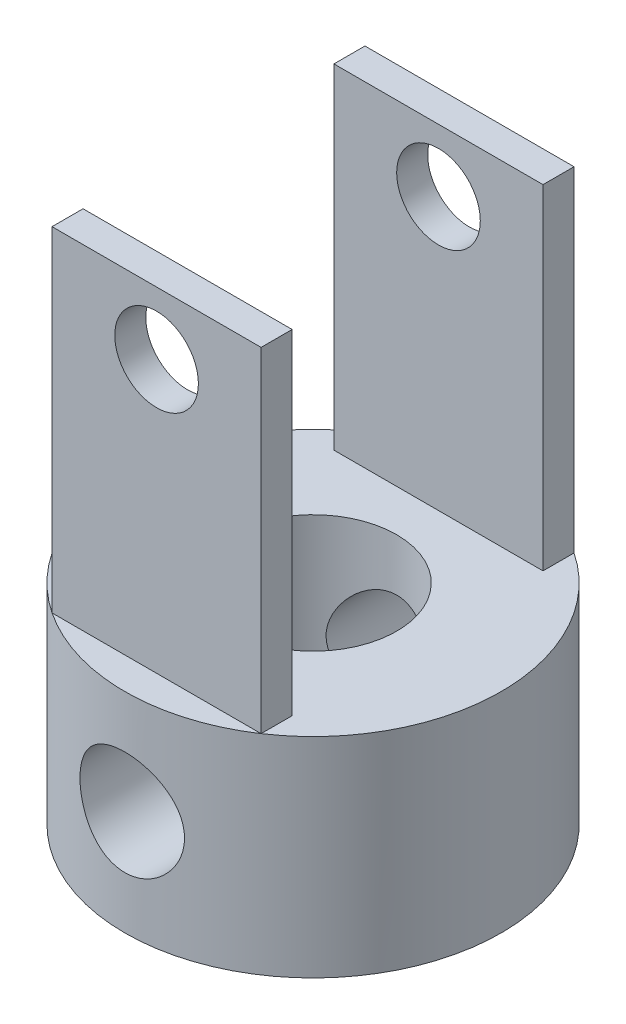
SolidWorks part; units mm, degrees
ref_plane "Front Plane" through (0, 0, 0) normal (0, 0, 1) x (1, 0, 0)
ref_plane "Top Plane" through (0, 0, 0) normal (0, 1, 0) x (1, 0, 0)
ref_plane "Right Plane" through (0, 0, 0) normal (1, 0, 0) x (0, 0, -1)
sketch "Sketch2" plane through (0, 0, 0) normal (0, 1, 0) x (1, 0, 0)
  circle A0 centre (0, 0) radius 4.5
  dimension "D1" = 9
extrude "Boss-Extrude1" add sketch "Sketch2" along normal blind 5
sketch "Sketch3" plane through (0, 5, 0) normal (0, 1, 0) x (1, 0, 0)
  line L0 (-4.5, 0) -> (4.5, 0) construction
  line L1 (-2.5, -3) -> (2.5, -3)
  line L2 (-2.5, 3.7417) -> (2.5, 3.7417)
  line L3 (-2.5, 3.7417) -> (-2.5, 3)
  line L4 (-2.5, 3) -> (2.5, 3)
  line L5 (2.5, 3.7417) -> (2.5, 3)
  line L6 (2.5, -3.7417) -> (2.5, -3)
  line L7 (-2.5, -3.7417) -> (2.5, -3.7417)
  line L8 (-2.5, -3.7417) -> (-2.5, -3)
  circle A0 centre (0, 0) radius 4.5 construction
  dimension "D1" = 3
  dimension "D2" = 5
extrude "Boss-Extrude2" add sketch "Sketch3" along normal blind 8
sketch "Sketch4" plane through (0, 0, 3.7417) normal (0, 0, 1) x (1, 0, 0)
  line L0 (0, 0) -> (0, 13) construction
  line L1 (-2.5, 13) -> (2.5, 13) construction
  line L2 (-4.5, 0) -> (4.5, 0) construction
  circle A0 centre (0, 11.5) radius 1
  dimension "D2" = 2
  dimension "D1" = 11.5
extrude "Cut-Extrude1" cut sketch "Sketch4" against normal up to surface (7.4833 mm away) up to face at (0, 9, -3.7417)
sketch "Sketch6" plane through (0, 0, 0) normal (0, -1, 0) x (1, 0, 0)
  circle A0 centre (0, 0) radius 2
  dimension "D1" = 4
extrude "Cut-Extrude2" cut sketch "Sketch6" against normal up to surface (5 mm away) up to face at (0, 5, 0)
ref_plane "Plane1" through (0, 0, 0) normal (0, 0, 1) x (1, 0, 0)
ref_plane "Plane2" through (0, 0, 4.5) normal (0, 0, 1) x (1, 0, 0)
sketch "Sketch8" plane through (0, 0, 4.5) normal (0, 0, 1) x (1, 0, 0)
  line L0 (0, 0) -> (0, 4) construction
  line L1 (-4.5, 0) -> (4.5, 0) construction
  line L2 (-4, 2.5) -> (4, 2.5) construction
  point P6 (0, 2.5)
  dimension "D1" = 2.5
  dimension "D2" = 4
  dimension "D3" = 8
  dimension "D4" = 4
hole_wizard "M3x0.5 Tapped Hole2" positions "Sketch8" profile "Sketch9" tap size "M3x0.5" standard "ANSI Metric"
sketch "Sketch9" plane through (0, 2.5, 4.5) normal (1, 0, 0) x (0, -1, 0)
  line L0 (0, 0) -> (0, 4.499)
  line L1 (0, 4.499) -> (1.25, 3.7479)
  line L2 (1.25, 3.7479) -> (1.25, 0)
  line L5 (1.25, 0) -> (0, 0)
  line L10 (0, 4.499) -> (-1.25, 3.7479) construction
  line L11 (0, -6.35) -> (0, 107.95) construction
  dimension "Tap Drill Dia." = 2.5
  dimension "Tap Drill Depth" = 4.499
  dimension "Drill Angle" = 118
cosmetic thread "Hole Thread2" parameters "D1"=6, "D2"=3
mirror "Mirror1" about plane through (0, 0, 0) normal (0, 0, 1) of "M3x0.5 Tapped Hole2"
cosmetic thread "Hole Thread3" parameters "D1"=6, "D2"=3
